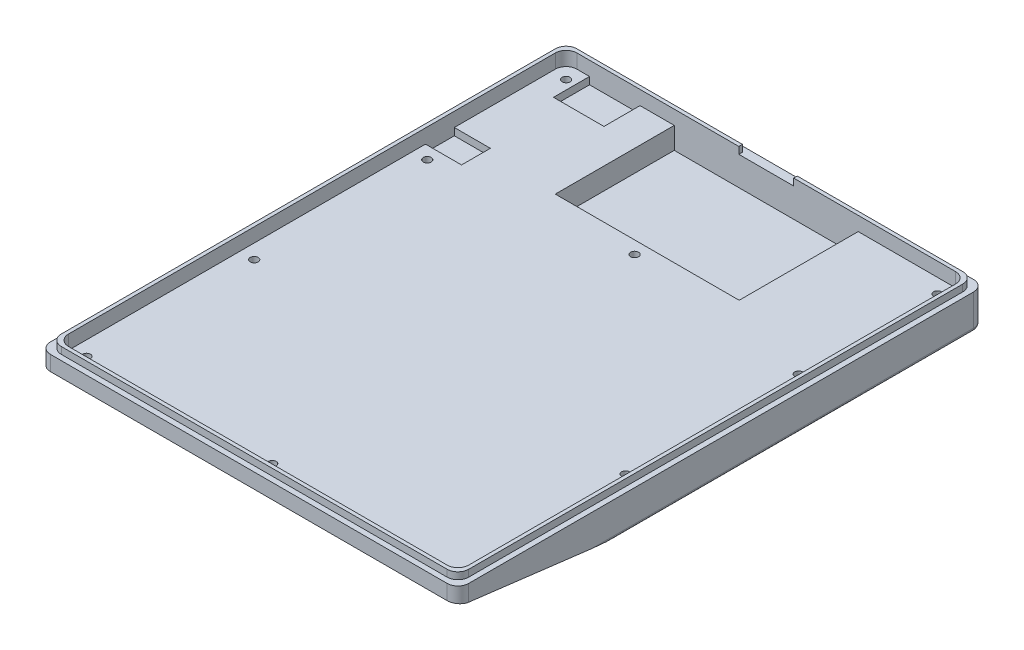
SolidWorks part; units mm, degrees
ref_plane "정면" through (0, 0, 0) normal (0, 0, 1) x (1, 0, 0)
ref_plane "윗면" through (0, 0, 0) normal (0, 1, 0) x (1, 0, 0)
ref_plane "우측면" through (0, 0, 0) normal (1, 0, 0) x (0, 0, -1)
sketch "스케치1" plane through (0, 0, 0) normal (0, 1, 0) x (1, 0, 0)
  line L1 (0, 0) -> (116, 0)
  line L2 (0, 0) -> (0, -146)
  line L3 (0, -146) -> (116, -146)
  line L4 (116, 0) -> (116, -146)
  dimension "D1" = 146
  dimension "D2" = 116
extrude "보스-돌출1" add sketch "스케치1" against normal blind 30
sketch "스케치2" plane through (0, 0, 0) normal (0, 1, 0) x (1, 0, 0)
  line L0 (0, -146) -> (116, -146) construction
  line L1 (0, 0) -> (0, -146) construction
  line L2 (116, -146) -> (116, 0) construction
  line L3 (116, 0) -> (0, 0) construction
  circle A0 centre (6.5, -139.5) radius 1.1
  circle A1 centre (109.5, -139.5) radius 1.1
  circle A2 centre (58, -139.5) radius 1.1
  circle A3 centre (6.5, -93) radius 1.1
  circle A4 centre (109.5, -93) radius 1.1
  circle A5 centre (6.5, -45) radius 1.1
  circle A6 centre (109.5, -45) radius 1.1
  circle A7 centre (58, -39) radius 1.1
  circle A8 centre (6.5, -6.5) radius 1.1
  circle A9 centre (109.5, -6.5) radius 1.1
  point P28 (0, 0)
  dimension "D1" = 2.2
  dimension "D4" = 2.2
  dimension "D7" = 2.2
  dimension "D10" = 2.2
  dimension "D12" = 2.2
  dimension "D13" = 2.2
  dimension "D15" = 2.2
  dimension "D16" = 2.2
  dimension "D18" = 2.2
  dimension "D21" = 2.2
  dimension "D2" = 6.5
  dimension "D3" = 6.5
  dimension "D5" = 6.5
  dimension "D6" = 6.5
  dimension "D8" = 58
  dimension "D9" = 58
  dimension "D11" = 46.5
  dimension "D14" = 48
  dimension "D17" = 6
  dimension "D19" = 6.5
  dimension "D20" = 6.5
  dimension "D22" = 6.5
  dimension "D23" = 46.5
  dimension "D24" = 48
extrude "컷-돌출3" cut sketch "스케치2" against normal through all
sketch "스케치5" plane through (0, 0, 0) normal (0, 1, 0) x (1, 0, 0)
  line L0 (0, -146) -> (116, -146) construction
  line L1 (3, -143) -> (113, -143)
  line L2 (3, -143) -> (3, -3)
  line L3 (3, -3) -> (113, -3)
  line L4 (113, -143) -> (113, -3)
  line L5 (0, 0) -> (0, -146) construction
  line L6 (116, 0) -> (0, 0) construction
  line L7 (116, -146) -> (116, 0) construction
  dimension "D1" = 110
  dimension "D2" = 140
  dimension "D3" = 3
  dimension "D4" = 3
  dimension "D5" = 3
  dimension "D6" = 3
extrude "컷-돌출4" cut sketch "스케치5" against normal blind 4 contours L2 L1 L4 L3
sketch "스케치6" plane through (116, 0, 0) normal (1, 0, 0) x (0, 0, -1)
  line L0 (-73, 0) -> (-73, -4) construction
  line L1 (-146, 0) -> (0, 0) construction
  line L2 (-73, -4) -> (0, -4) construction
  line L3 (0, -30) -> (0, 0) construction
  line L4 (-73, -4) -> (-146, -4) construction
  line L5 (-146, -30) -> (-146, 0) construction
  line L6 (-146, -4) -> (-143, -4) construction
  line L7 (-149.1045, -5.7692) -> (15.482, -25.9779)
  line L8 (-149.1045, -5.7692) -> (-150.1175, -37.1746)
  line L9 (-150.1175, -37.1746) -> (15.482, -42.5162)
  line L10 (15.482, -42.5162) -> (15.482, -25.9779)
  dimension "D1" = 4
  dimension "D2" = 3
  dimension "D3" = 7
  dimension "D4" = 2.5
extrude "컷-돌출5" cut sketch "스케치6" against normal through all
sketch "스케치9" plane through (0, -4, 0) normal (0, 1, 0) x (1, 0, 0)
  line L0 (58, -3) -> (58, -37.9) construction
  line L1 (3, -3) -> (113, -3) construction
  line L2 (3, -3) -> (113, -3) construction
  line L9 (32.5, -3) -> (83.5, -3)
  line L10 (32.5, -3) -> (32.5, -35.5)
  line L11 (32.5, -35.5) -> (83.5, -35.5)
  line L12 (83.5, -3) -> (83.5, -35.5)
  circle A0 centre (58, -39) radius 1.1 construction
  point P6 (58, -20.45)
  dimension "D3" = 32.5
extrude "컷-돌출7" cut sketch "스케치9" against normal blind 6
sketch "스케치13" plane through (0, 0, 0) normal (0, 1, 0) x (1, 0, 0)
  line L12 (2.5, -2.5) -> (2.5, -143.5)
  line L13 (2.5, -143.5) -> (113.5, -143.5)
  line L14 (113.5, -143.5) -> (113.5, -2.5)
  line L15 (113.5, -2.5) -> (2.5, -2.5)
  line L16 (2.5, -2.5) -> (2.5, -143.5)
  line L17 (2.5, -143.5) -> (113.5, -143.5)
  line L18 (113.5, -143.5) -> (113.5, -2.5)
  line L19 (113.5, -2.5) -> (2.5, -2.5)
  dimension "D1" = 2.5
extrude "컷-돌출11" cut sketch "스케치13" against normal up to vertex (4 mm away)
sketch "스케치15" plane through (0, -4, 0) normal (0, 1, 0) x (1, 0, 0)
  line L0 (113.5, -2.5) -> (2.5, -2.5) construction
  line L1 (32.5, -3) -> (83.5, -3)
  line L2 (32.5, -3) -> (32.5, -2.5)
  line L3 (32.5, -2.5) -> (83.5, -2.5)
  line L4 (83.5, -3) -> (83.5, -2.5)
extrude "컷-돌출12" cut sketch "스케치15" against normal up to vertex (6 mm away)
sketch "스케치16" plane through (0, 0, 0) normal (0, 1, 0) x (1, 0, 0)
  line L1 (0, 0) -> (116, 0)
  line L2 (0, 0) -> (0, -146)
  line L3 (0, -146) -> (116, -146)
  line L4 (116, 0) -> (116, -146)
  line L12 (1.5, -1.5) -> (1.5, -144.5)
  line L13 (1.5, -144.5) -> (114.5, -144.5)
  line L14 (114.5, -144.5) -> (114.5, -1.5)
  line L15 (114.5, -1.5) -> (1.5, -1.5)
  line L16 (1.5, -1.5) -> (1.5, -144.5)
  line L17 (1.5, -144.5) -> (114.5, -144.5)
  line L18 (114.5, -144.5) -> (114.5, -1.5)
  line L19 (114.5, -1.5) -> (1.5, -1.5)
  dimension "D1" = 1.5
extrude "컷-돌출13" cut sketch "스케치16" against normal blind 2
sketch "스케치17" plane through (0, -4, 0) normal (0, 1, 0) x (1, 0, 0)
  line L0 (2.5, -2.5) -> (9, -2.5) construction
  line L1 (113.5, -2.5) -> (2.5, -2.5) construction
  line L2 (2.5, -2.5) -> (2.5, -143.5) construction
  line L3 (9, -2.5) -> (23, -2.5)
  line L4 (9, -2.5) -> (9, -12.5)
  line L5 (9, -12.5) -> (23, -12.5)
  line L6 (23, -2.5) -> (23, -12.5)
  line L7 (2.5, -41.5) -> (12.5, -41.5)
  line L8 (2.5, -41.5) -> (2.5, -33.5)
  line L9 (2.5, -33.5) -> (12.5, -33.5)
  line L10 (12.5, -41.5) -> (12.5, -33.5)
  dimension "D1" = 6.5
  dimension "D2" = 14
  dimension "D3" = 10
  dimension "D4" = 39
  dimension "D5" = 8
  dimension "D6" = 10
extrude "컷-돌출14" cut sketch "스케치17" against normal blind 2
sketch "스케치18" plane through (0, 0, 0) normal (0, 1, 0) x (1, 0, 0)
  line L1 (1.5, -1.5) -> (114.5, -1.5)
  line L2 (1.5, -1.5) -> (1.5, -144.5)
  line L3 (1.5, -144.5) -> (114.5, -144.5)
  line L4 (114.5, -1.5) -> (114.5, -144.5)
extrude "컷-돌출15" cut sketch "스케치18" against normal blind 0.1
sketch "스케치19" plane through (0, 0, 1.5) normal (0, 0, -1) x (-1, 0, 0)
  line L0 (-58, -0.1) -> (-58, -1.1) construction
  line L1 (-114.5, -0.1) -> (-1.5, -0.1) construction
  line L3 (-65.4, -2.1) -> (-50.6, -2.1)
  line L4 (-65.4, -2.1) -> (-65.4, -0.1)
  line L5 (-65.4, -0.1) -> (-50.6, -0.1)
  line L6 (-50.6, -2.1) -> (-50.6, -0.1)
  line L7 (-65.4, -2.1) -> (-50.6, -0.1) construction
  line L8 (-65.4, -0.1) -> (-50.6, -2.1) construction
  dimension "D1" = 1
  dimension "D2" = 14.8
extrude "컷-돌출17" cut sketch "스케치19" against normal blind 1.5
sketch "스케치20" plane through (0, -2.1, 0) normal (0, 1, 0) x (1, 0, 0)
  line L1 (50.6, -1.5) -> (65.4, -1.5)
  line L2 (50.6, -1.5) -> (50.6, -2.5)
  line L3 (50.6, -2.5) -> (65.4, -2.5)
  line L4 (65.4, -1.5) -> (65.4, -2.5)
extrude "보스-돌출4" add sketch "스케치20" along normal up to vertex
sketch "스케치21" plane through (0, 0, 1.5) normal (0, 0, -1) x (-1, 0, 0)
  line L0 (-65.4, -1.05) -> (-50.6, -1.05) construction
  line L1 (-65.4, -0.1) -> (-65.4, -2) construction
  line L2 (-50.6, -2) -> (-50.6, -0.1) construction
  line L3 (-50.6, -0.1) -> (-1.5, -0.1) construction
  line L4 (-65.6, -2) -> (-50.4, -2)
  line L5 (-65.6, -2) -> (-65.6, -0.1)
  line L6 (-65.6, -0.1) -> (-50.4, -0.1)
  line L7 (-50.4, -2) -> (-50.4, -0.1)
  line L8 (-65.6, -2) -> (-50.4, -0.1) construction
  line L9 (-65.6, -0.1) -> (-50.4, -2) construction
  point P6 (-58, -1.05)
  dimension "D1" = 15.2
extrude "컷-돌출18" cut sketch "스케치21" against normal blind 1
sketch "스케치22" plane through (0, -4, 0) normal (0, 1, 0) x (1, 0, 0)
  circle A0 centre (6.5, -6.5) radius 2
  circle A1 centre (109.5, -6.5) radius 2
  circle A2 centre (109.5, -45) radius 2
  circle A3 centre (58, -39) radius 2
  circle A4 centre (6.5, -45) radius 2
  circle A5 centre (6.5, -93) radius 2
  circle A6 centre (6.5, -139.5) radius 2
  circle A7 centre (58, -139.5) radius 2
  circle A8 centre (109.5, -139.5) radius 2
  circle A9 centre (109.5, -93) radius 2
  dimension "D1" = 4
  dimension "D2" = 4
  dimension "D3" = 4
  dimension "D4" = 4
  dimension "D5" = 4
  dimension "D6" = 4
  dimension "D7" = 4
  dimension "D8" = 4
  dimension "D9" = 4
  dimension "D10" = 4
extrude "컷-돌출19" cut sketch "스케치22" against normal through all
sketch "스케치23" plane through (0, -4, 0) normal (0, 1, 0) x (1, 0, 0)
  circle A0 centre (6.5, -6.5) radius 2
  circle A1 centre (6.5, -6.5) radius 1.1
  circle A2 centre (6.5, -45) radius 2
  circle A3 centre (6.5, -45) radius 1.1
  circle A4 centre (6.5, -93) radius 2
  circle A5 centre (6.5, -93) radius 1.1
  circle A6 centre (109.5, -93) radius 2
  circle A7 centre (109.5, -93) radius 1.1
  circle A8 centre (109.5, -45) radius 2
  circle A9 centre (109.5, -45) radius 1.1
  circle A10 centre (58, -39) radius 2
  circle A11 centre (58, -39) radius 1.1
  circle A12 centre (109.5, -6.5) radius 2
  circle A13 centre (109.5, -6.5) radius 1.1
  dimension "D1" = 2.2
  dimension "D2" = 2.2
  dimension "D3" = 2.2
  dimension "D4" = 2.2
  dimension "D5" = 2.2
  dimension "D6" = 2.2
  dimension "D7" = 2.2
extrude "보스-돌출5" add sketch "스케치23" against normal blind 5.5
sketch "스케치24" plane through (0, -4, 0) normal (0, 1, 0) x (1, 0, 0)
  circle A0 centre (6.5, -139.5) radius 2
  circle A1 centre (6.5, -139.5) radius 1.1
  circle A2 centre (58, -139.5) radius 2
  circle A3 centre (58, -139.5) radius 1.1
  circle A4 centre (109.5, -139.5) radius 2
  circle A5 centre (109.5, -139.5) radius 1.1
  dimension "D1" = 2.2
  dimension "D2" = 2.2
  dimension "D3" = 2.2
extrude "보스-돌출6" add sketch "스케치24" against normal blind 1.2
sketch "스케치26" plane through (0, -23.7194, 2.9124) normal (0, -0.9925, 0.1219) x (1, 0, 0)
  line L1 (0, 144.1622) -> (12, 144.1622)
  line L2 (0, 144.1622) -> (0, 132.1622)
  line L3 (0, 132.1622) -> (12, 132.1622)
  line L4 (12, 144.1622) -> (12, 132.1622)
  line L5 (116, -2.9342) -> (104, -2.9342)
  line L6 (116, -2.9342) -> (116, 9.0658)
  line L7 (116, 9.0658) -> (104, 9.0658)
  line L8 (104, -2.9342) -> (104, 9.0658)
  circle A0 centre (12, 132.1622) radius 4.05
  circle A1 centre (104, 9.0658) radius 4.05
  circle A2 centre (104, 132.1622) radius 4.05
  circle A3 centre (12, 9.0658) radius 4.05
  dimension "D3" = 8.1
  dimension "D6" = 8.1
  dimension "D7" = 8.1
  dimension "D8" = 8.1
  dimension "D1" = 12
  dimension "D2" = 12
  dimension "D4" = 12
  dimension "D5" = 12
extrude "컷-돌출20" cut sketch "스케치26" against normal blind 1.5 contours A3 | L7 A1 L8 | L8 A1 L7 | L4 A0 L3 | L3 A0 L4 | A2
sketch "스케치27" plane through (116, 0, 0) normal (1, 0, 0) x (0, 0, -1)
  line L0 (-73, -2) -> (-73, -4) construction
  line L1 (-146, -2) -> (0, -2) construction
  line L2 (-73, -4) -> (0, -4) construction
  line L3 (0, -24.077) -> (0, -2) construction
  line L4 (-73, -4) -> (-146, -4.0752) construction
  line L5 (-146, -6.1504) -> (-146, -2) construction
  line L6 (-146, -6.1504) -> (0, -6.1504) construction
  line L7 (-73, -4) -> (-73, -9.5) construction
  line L8 (-73, -9.5) -> (0, -9.5) construction
  line L9 (-73, -9.5) -> (-146, -9.5) construction
  line L10 (-73, -11.7) -> (0, -11.7)
  line L11 (-73, -9.5) -> (-73, -11.7) construction
  line L12 (-73, -11.7) -> (-146, -11.7)
  line L13 (-146, -11.7) -> (-146, -22.1749)
  line L14 (0, -11.7) -> (0, -27.4963)
  line L15 (0, -27.4963) -> (-146, -27.4963)
  line L16 (-146, -27.4963) -> (-146, -22.1749)
  point P13 (0, 0)
  point P24 (0, 0)
  point P25 (0, 0)
  dimension "D1" = 2
  dimension "D2" = 5.5
  dimension "D3" = 2.2
sketch "스케치32" plane through (0, 0, 0) normal (0, 0, -1) x (-1, 0, 0)
  line L1 (-116, -24.077) -> (0, -24.077)
  line L2 (-116, -24.077) -> (-116, -34.077)
  line L3 (-116, -34.077) -> (0, -34.077)
  line L4 (0, -24.077) -> (0, -34.077)
  dimension "D1" = 10
extrude "보스-돌출7" add sketch "스케치32" along normal blind 10 separate body
sketch "스케치33" plane through (0, -34.077, 0) normal (0, -1, 0) x (1, 0, 0)
  line L0 (58, 146) -> (58, 126) construction
  line L1 (0, 0) -> (116, 0)
  line L2 (0, 0) -> (0, 146)
  line L3 (0, 146) -> (116, 146)
  line L4 (116, 0) -> (116, 146)
  line L5 (0, -10) -> (116, -10)
  line L6 (0, -10) -> (0, 0)
  line L7 (0, 0) -> (116, 0)
  line L8 (116, -10) -> (116, 0)
  line L9 (0, 126) -> (116, 126) construction
  line L10 (58, 126) -> (58, 66)
  line L11 (58, 66) -> (98, 66) construction
  line L12 (58, 66) -> (18, 66) construction
  line L13 (0, 126) -> (18, 66)
  line L14 (18, 66) -> (18, 0)
  line L15 (116, 126) -> (98, 66)
  line L16 (98, 66) -> (98, 0)
  line L17 (98, 0) -> (116, 0)
  line L18 (116, 0) -> (116, 126)
  line L19 (0, 126) -> (0, 0)
  line L20 (0, 0) -> (18, 0)
  line L22 (0, 0) -> (116, 0)
  line L23 (0, 0) -> (0, -10)
  line L24 (0, -10) -> (116, -10)
  line L25 (116, 0) -> (116, -10)
  dimension "D1" = 20
  dimension "D2" = 60
  dimension "D3" = 40
  dimension "D4" = 40
extrude "컷-돌출22" cut sketch "스케치33" against normal up to vertex (22.377 mm away) contours L15 L16 L4 | L14 L13 L2 L7 | L18 L15 L7 L16 L17
fillet "필렛16" radius 3 12 edges at (113.5, -2.05, 2.5) (114.5, -1.05, 1.5) (116, -6.85, 0) (1.5, -1.05, 1.5) (2.5, -2.05, 2.5) (0, -6.85, 0) (2.5, -2.05, 143.5) (0, -4.0752, 146) (1.5, -1.05, 144.5) (113.5, -2.05, 143.5) (114.5, -1.05, 144.5) (116, -4.0752, 146)
fillet "필렛18" radius 1 6 edges at (10.5, -11.7, 0) (0, -11.7, 51.9012) (116, -11.7, 51.9012) (105.5, -11.7, 0) (115.1213, -11.7, 0.8787) (0.8787, -11.7, 0.8787)
fillet "필렛25" radius 180 1 edges at (98, -13.8366, 66)
fillet "필렛26" radius 180 1 edges at (18, -13.8366, 66)
fillet "필렛27" radius 3 2 edges at (18, -17.3885, 0) (98, -17.3885, 0)
sketch "스케치34" plane through (0, -23.7194, 2.9124) normal (0, -0.9925, 0.1219) x (1, 0, 0)
  line L1 (21, -2.9342) -> (18, -2.9342)
  line L2 (21, -2.9342) -> (21, 0.0883)
  line L3 (21, 0.0883) -> (18, 0.0883)
  line L4 (18, -2.9342) -> (18, 0.0883)
  line L5 (98, 0.0883) -> (95, 0.0883)
  line L6 (98, 0.0883) -> (98, -2.9342)
  line L7 (98, -2.9342) -> (95, -2.9342)
  line L8 (95, 0.0883) -> (95, -2.9342)
  line L9 (98, -2.9342) -> (88, -2.9342)
  line L10 (98, -2.9342) -> (98, 7.0658)
  line L11 (98, 7.0658) -> (88, 7.0658)
  line L12 (88, -2.9342) -> (88, 7.0658)
  line L13 (18, -2.9342) -> (28, -2.9342)
  line L14 (18, -2.9342) -> (18, 7.0658)
  line L15 (18, 7.0658) -> (28, 7.0658)
  line L16 (28, -2.9342) -> (28, 7.0658)
  circle A0 centre (28, 7.0658) radius 4.05
  circle A1 centre (88, 7.0658) radius 4.05
  dimension "D5" = 8.1
  dimension "D6" = 8.1
  dimension "D1" = 10
  dimension "D2" = 10
  dimension "D3" = 10
  dimension "D4" = 10
extrude "컷-돌출23" cut sketch "스케치34" against normal blind 1.5 contours L16 A0 L15 | L15 A0 L16 | L11 A1 L12 | L12 A1 L11
